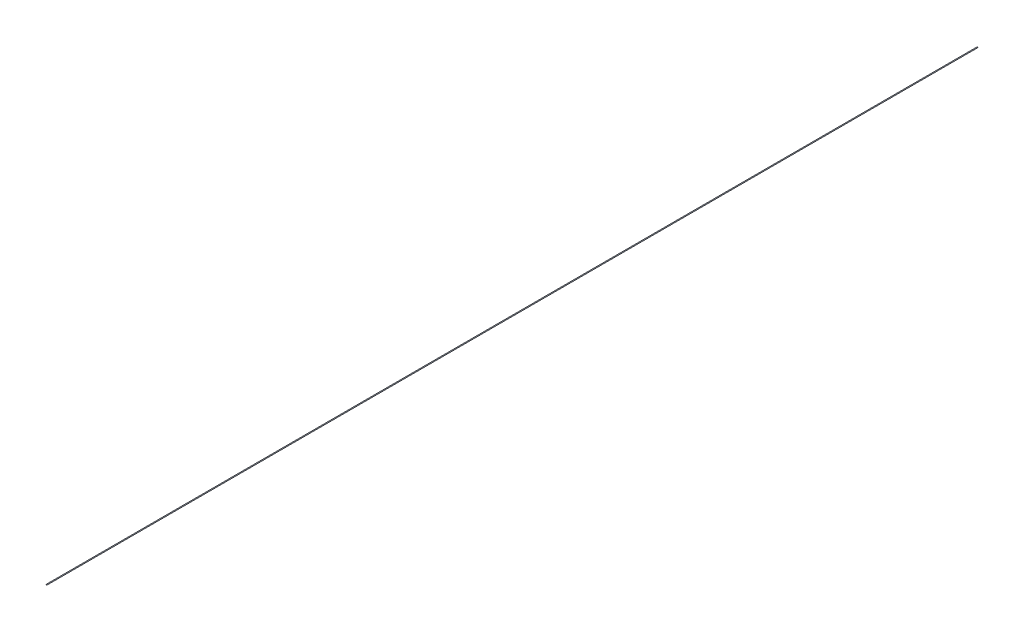
SolidWorks part; units mm, degrees
ref_plane "Front Plane" through (0, 0, 0) normal (0, 0, 1) x (1, 0, 0)
ref_plane "Top Plane" through (0, 0, 0) normal (0, 1, 0) x (1, 0, 0)
ref_plane "Right Plane" through (0, 0, 0) normal (1, 0, 0) x (0, 0, -1)
sketch "Sketch1" plane through (0, 0, 0) normal (0, 0, 1) x (1, 0, 0)
  circle A0 centre (0, 0) radius 3.175
  dimension "D1" = 6.35
extrude "Extrude1" add sketch "Sketch1" along normal blind 7620
sketch "Sketch2" plane through (0, 0, 0) normal (0, 0, -1) x (-1, 0, 0)
  point P0 (0, 0)
sketch "Sketch3" plane through (0, 0, 7620) normal (0, 0, 1) x (1, 0, 0)
  point P0 (0, 0)
